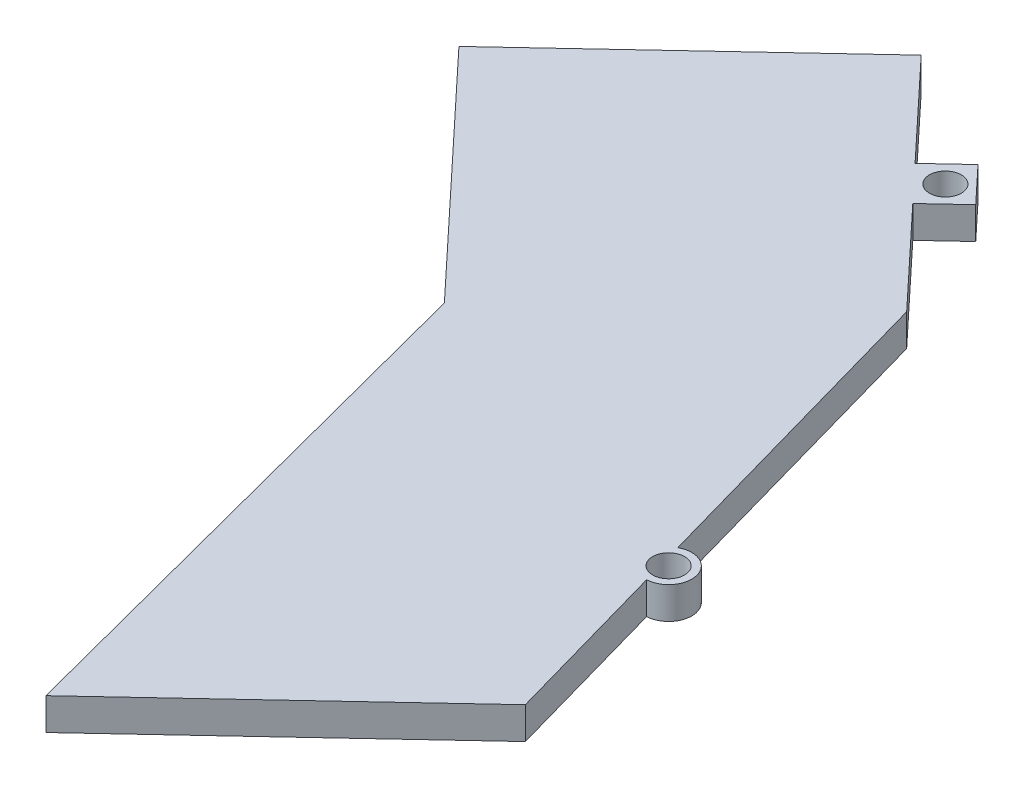
SolidWorks part; units mm, degrees
ref_plane "Front Plane" through (0, 0, 0) normal (0, 0, 1) x (1, 0, 0)
ref_plane "Top Plane" through (0, 0, 0) normal (0, 1, 0) x (1, 0, 0)
ref_plane "Right Plane" through (0, 0, 0) normal (1, 0, 0) x (0, 0, -1)
sketch "Sketch1" plane through (0, 0, 0) normal (0, 1, 0) x (1, 0, 0)
  line L0 (59.9923, -52.5624) -> (50.5252, -18.985)
  line L1 (30.2184, 53.0382) -> (12.1909, 72.2854)
  line L2 (-12.5214, 98.6696) -> (-59.9923, 54.2068)
  line L3 (-59.9923, 54.2068) -> (-17.2525, 8.5754)
  line L4 (-17.2525, 8.5754) -> (10.7658, -98.6696)
  line L5 (59.9923, -52.5624) -> (10.7658, -98.6696)
  line L6 (48.0929, -10.358) -> (30.2184, 53.0382)
  line L7 (18.6535, 78.3386) -> (12.1909, 72.2854)
  line L8 (18.6535, 78.3386) -> (11.9688, 85.4755)
  line L9 (11.9688, 85.4755) -> (5.5061, 79.4224)
  line L10 (5.5061, 79.4224) -> (-12.5214, 98.6696)
  line L11 (-59.9923, 54.2068) -> (0, 0) construction
  line L12 (0, 0) -> (30.2184, 53.0382) construction
  line L13 (0, 0) -> (10.7658, -98.6696) construction
  line L14 (0, 0) -> (59.9923, -52.5624) construction
  line L15 (-12.5214, 98.6696) -> (0, 0) construction
  line L16 (5.5061, 79.4224) -> (12.1909, 72.2854) construction
  line L17 (12.1909, 72.2854) -> (0, 0) construction
  line L18 (-17.2525, 8.5754) -> (0, 0) construction
  line L19 (48.0929, -10.358) -> (39.8525, -15.8402) construction
  line L20 (39.8525, -15.8402) -> (50.5252, -18.985) construction
  line L21 (39.8525, -15.8402) -> (0, 0) construction
  line L22 (48.0929, -10.358) -> (0, 0) construction
  line L23 (39.8525, -15.8402) -> (59.9923, -52.5624) construction
  circle A0 centre (12.0799, 78.8805) radius 3.175
  arc A1 (50.5252, -18.985) -> (48.0929, -10.358) centre (50.3089, -14.3896) ccw
  circle A2 centre (50.3089, -14.3896) radius 3.175
  dimension "D1" = 6.35
  dimension "D2" = 6.35
  dimension "D3" = 65.0417
  dimension "D4" = 62.5214
  dimension "D5" = 9.7786
  dimension "D6" = 110.8445
  dimension "D7" = 98.6696
  dimension "D8" = 67.4471
extrude "Boss-Extrude1" add sketch "Sketch1" along normal blind 6.35
